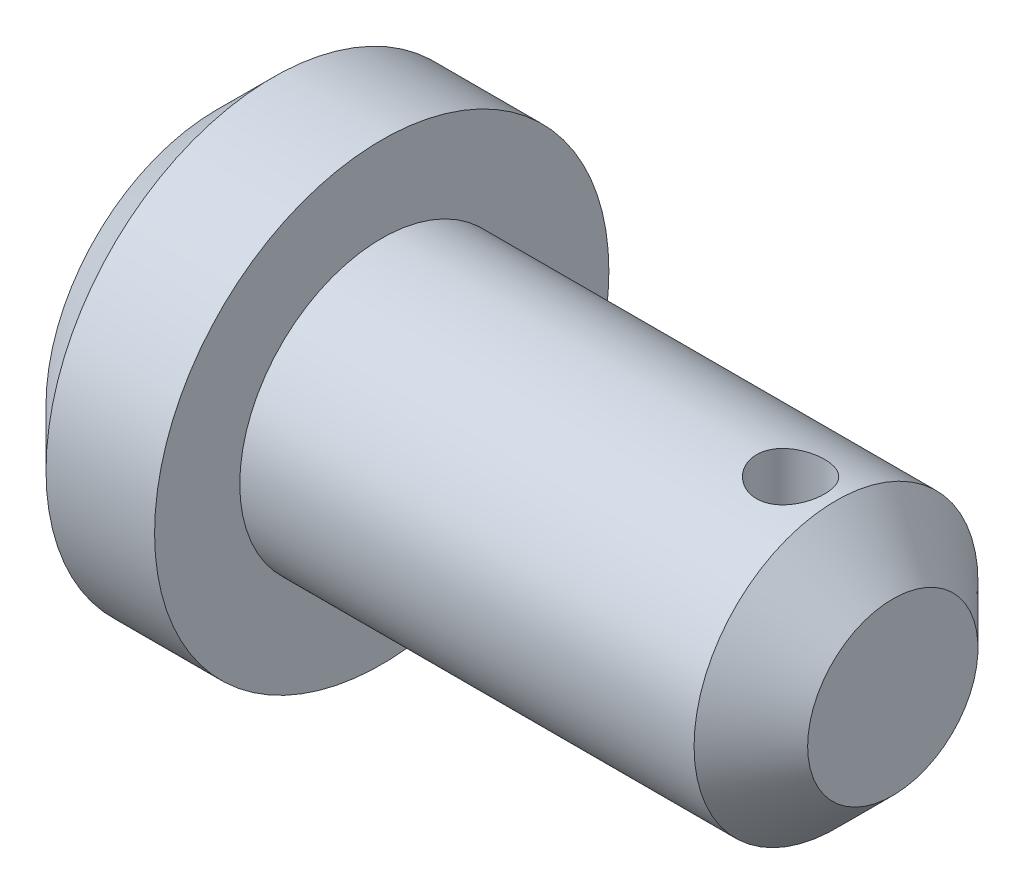
SolidWorks part; units mm, degrees
ref_plane "Front Plane" through (0, 0, 0) normal (0, 0, 1) x (1, 0, 0)
ref_plane "Top Plane" through (0, 0, 0) normal (0, 1, 0) x (1, 0, 0)
ref_plane "Right Plane" through (0, 0, 0) normal (1, 0, 0) x (0, 0, -1)
sketch "Sketch1" plane through (0, 0, 0) normal (0, 1, 0) x (1, 0, 0)
  line L0 (0, 0) -> (150, 0) construction
  line L1 (0, 25) -> (0, 40)
  line L2 (0, 40) -> (-19.1205, 40)
  line L3 (-29.1205, 30) -> (-29.1205, 0)
  line L5 (-29.1205, 0) -> (0, 0)
  line L10 (0, 25) -> (80, 25)
  line L14 (90, 15) -> (90, 0)
  line L15 (90, 0) -> (0, 0)
  line L16 (80, 25) -> (90, 15)
  line L17 (-29.1205, 30) -> (-19.1205, 40)
  dimension "D1" = 90
  dimension "D2" = 50
  dimension "D3" = 80
  dimension "D4" = 45
  dimension "D5" = 10
  dimension "D6" = 19.1205
  dimension "D7" = 45
  dimension "D8" = 10
revolve "Revolve2" add sketch "Sketch1" angle 360 about L0
sketch "Sketch4" plane through (0, 0, 0) normal (0, 1, 0) x (1, 0, 0)
  line L0 (0, -25) -> (0, 25) construction
  circle A0 centre (72, 0) radius 6
  dimension "D1" = 72
  dimension "D2" = 12
extrude "Cut-Extrude3" cut sketch "Sketch4" against normal through all both and the other way through all
